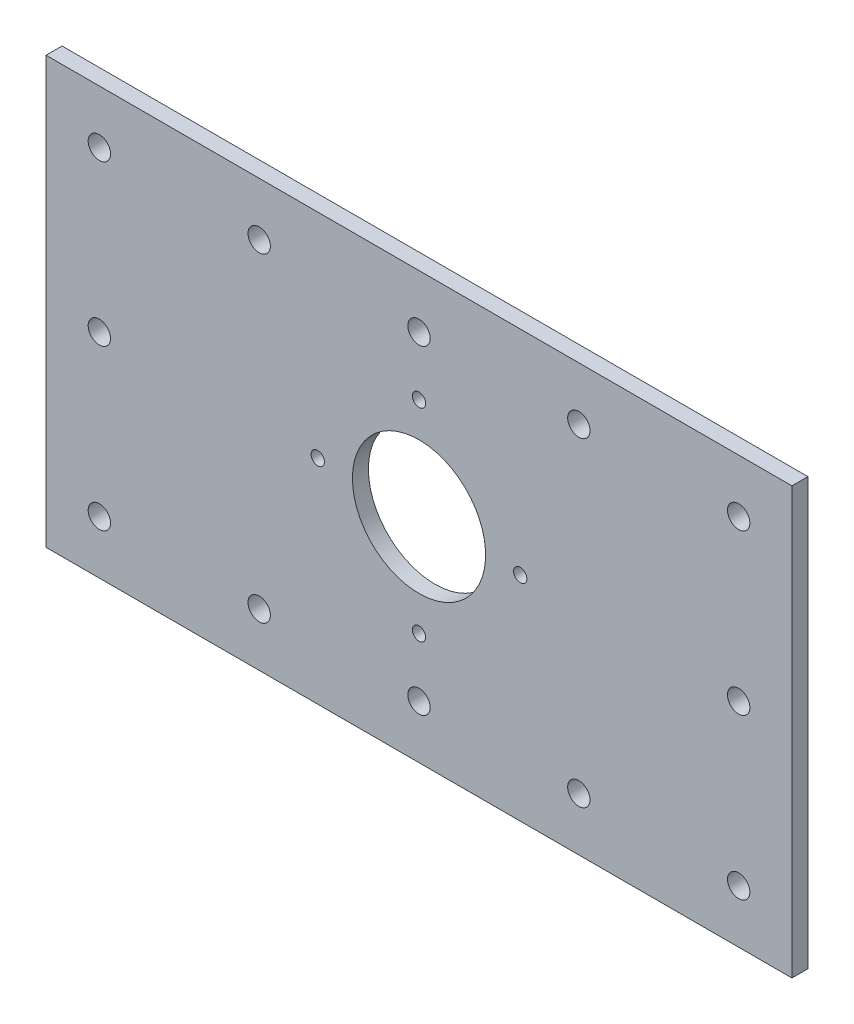
SolidWorks part; units mm, degrees
material "黑玻纤板"
ref_plane "前视基准面" through (0, 0, 0) normal (0, 0, 1) x (1, 0, 0)
ref_plane "上视基准面" through (0, 0, 0) normal (0, 1, 0) x (1, 0, 0)
ref_plane "右视基准面" through (0, 0, 0) normal (1, 0, 0) x (0, 0, -1)
sketch "草图1" plane through (0, 0, 0) normal (0, 0, 1) x (1, 0, 0)
  line L1 (-70, 40) -> (70, 40)
  line L2 (-70, 40) -> (-70, -40)
  line L3 (-70, -40) -> (70, -40)
  line L4 (70, 40) -> (70, -40)
  line L5 (-70, 40) -> (70, -40) construction
  line L6 (-70, -40) -> (70, 40) construction
  point P0 (0, 0)
  dimension "D1" = 140
  dimension "D2" = 80
extrude "凸台-拉伸1" add sketch "草图1" along normal blind 3
sketch "草图2" plane through (0, 0, 3) normal (0, 0, 1) x (1, 0, 0)
  line L0 (70, 30) -> (-70, 30) construction
  line L1 (70, -40) -> (70, 40) construction
  line L2 (-70, 40) -> (-70, -40) construction
  line L3 (70, 40) -> (-70, 40) construction
  line L4 (-60, 40) -> (-60, -40) construction
  line L5 (-70, -40) -> (70, -40) construction
  line L6 (0, 40) -> (0, -40) construction
  line L7 (60, 40) -> (60, -40) construction
  line L8 (70, 0) -> (-70, 0) construction
  line L9 (70, -30) -> (-70, -30) construction
  circle A0 centre (-60, 30) radius 2.1
  circle A1 centre (-30, 30) radius 2.1
  circle A2 centre (0, 30) radius 2.1
  circle A3 centre (30, 30) radius 2.1
  circle A4 centre (60, 30) radius 2.1
  circle A5 centre (-60, 0) radius 2.1
  circle A6 centre (-60, -30) radius 2.1
  circle A7 centre (-60, -60) radius 2.1
  circle A8 centre (-60, -90) radius 2.1
  circle A9 centre (-60, -120) radius 2.1
  circle A10 centre (-60, -150) radius 2.1
  circle A11 centre (-60, -180) radius 2.1
  circle A12 centre (-60, -210) radius 2.1
  circle A13 centre (60, -210) radius 2.1
  circle A14 centre (60, -180) radius 2.1
  circle A15 centre (60, -150) radius 2.1
  circle A16 centre (60, -120) radius 2.1
  circle A17 centre (60, -90) radius 2.1
  circle A18 centre (60, -60) radius 2.1
  circle A19 centre (60, -30) radius 2.1
  circle A20 centre (60, 0) radius 2.1
  circle A21 centre (60, 30) radius 2.1
  circle A22 centre (30, -30) radius 2.1
  circle A23 centre (0, -30) radius 2.1
  circle A24 centre (-30, -30) radius 2.1
  dimension "D3" = 4.2
  dimension "D4" = 30
  dimension "D7" = 30
  dimension "D1" = 10
  dimension "D2" = 10
  dimension "D5" = 30
  dimension "D6" = 30
  dimension "D8" = 9
extrude "切除-拉伸1" cut sketch "草图2" against normal through all contours A24 | A12 | A11 | A23 | A22 | A13 | A14 | A15 | A10 | A9 | A8 | A16 | A17 | A18 | A19 | A20 | A3 | A2 | A1 | A0 | A5 | A7 | A6 | A4
sketch "草图3" plane through (0, 0, 0) normal (0, 0, -1) x (-1, 0, 0)
  line L0 (0, 40) -> (0, -40) construction
  line L1 (-70, 40) -> (70, 40) construction
  line L2 (70, -40) -> (-70, -40) construction
  circle A0 centre (0, 0) radius 19 construction
  circle A1 centre (19, 0) radius 1.25
  circle A2 centre (0, -19) radius 1.25
  circle A3 centre (-19, 0) radius 1.25
  circle A4 centre (0, 19) radius 1.25
  point P20 (0, 0)
  dimension "D1" = 38
  dimension "D2" = 2.5
  dimension "D3" = 4
extrude "切除-拉伸2" cut sketch "草图3" against normal through all both and the other way through all
sketch "草图4" plane through (0, 0, 0) normal (0, 0, -1) x (-1, 0, 0)
  circle A0 centre (0, 0) radius 12.5
  dimension "D1" = 25
extrude "切除-拉伸3" cut sketch "草图4" against normal through all both and the other way through all
